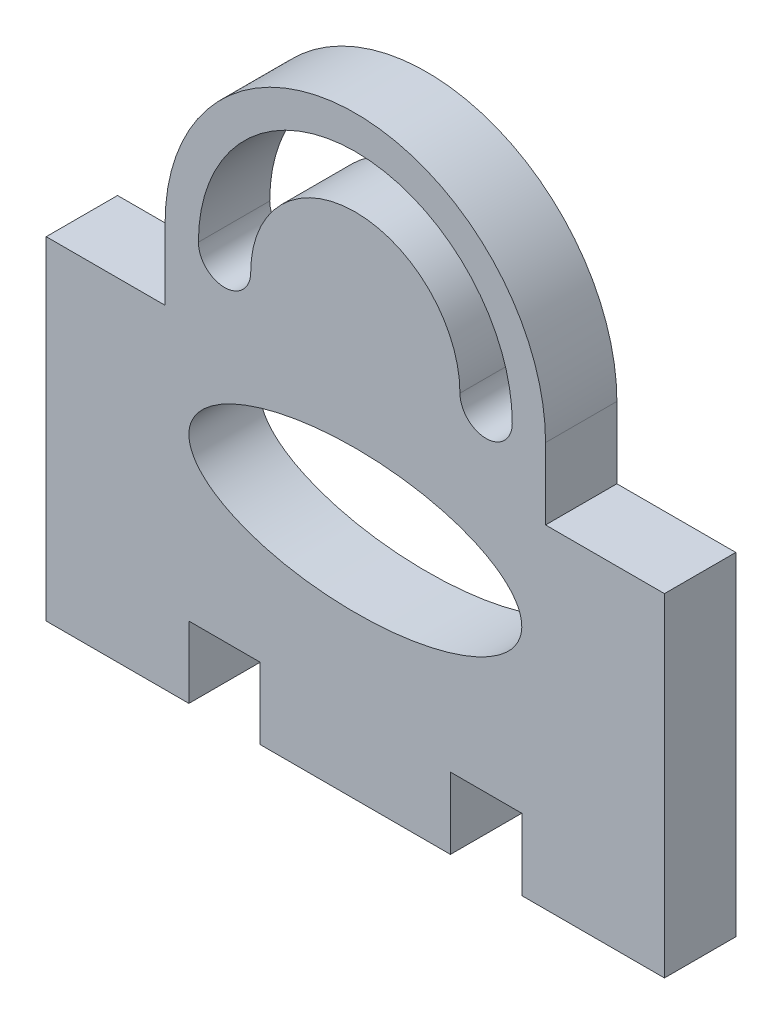
SolidWorks part; units mm, degrees
ref_plane "Front Plane" through (0, 0, 0) normal (0, 0, 1) x (1, 0, 0)
ref_plane "Top Plane" through (0, 0, 0) normal (0, 1, 0) x (1, 0, 0)
ref_plane "Right Plane" through (0, 0, 0) normal (1, 0, 0) x (0, 0, -1)
sketch "Sketch1" plane through (0, 0, 0) normal (0, 0, 1) x (1, 0, 0)
  line L0 (130, -70) -> (70, -70)
  line L2 (130, -70) -> (130, 70)
  line L3 (130, 70) -> (80, 70)
  line L4 (-130, -70) -> (-130, 70)
  line L5 (40, -40) -> (40, -70)
  line L6 (70, -40) -> (70, -70)
  line L8 (-130, -70) -> (-70, -70)
  line L9 (70, -40) -> (40, -40)
  line L10 (40, -70) -> (-40, -70)
  line L11 (-70, -70) -> (-70, -40)
  line L13 (-40, -70) -> (-40, -40)
  line L14 (-40, -40) -> (-70, -40)
  line L16 (0, 0) -> (0, 232.6311) construction
  line L17 (-80, 70) -> (-130, 70)
  line L18 (-80, 100) -> (-80, 70)
  line L19 (80, 100) -> (80, 70)
  line L20 (-149.4428, 28.0053) -> (199.022, 28.0053) construction
  arc A1 (80, 100) -> (-80, 100) centre (0, 100) ccw
  arc A2 (-55, 100) -> (55, 100) centre (0, 100) cw construction
  arc A3 (66, 100) -> (-66, 100) centre (0, 100) ccw
  arc A4 (44, 100) -> (-44, 100) centre (0, 100) ccw
  arc A5 (44, 100) -> (66, 100) centre (55, 100) ccw
  arc A6 (-66, 100) -> (-44, 100) centre (-55, 100) ccw
  ellipse E0 centre (0, 28.0053) end of major axis (-70, 28.0053) minor radius 30
  point P0 (0, 0)
  point P26 (0, 164.5804)
  point P32 (0, 0)
  dimension "D10" = 160
  dimension "D12" = 22
  dimension "D11" = 55
  dimension "D1" = 140
  dimension "D2" = 260
  dimension "D3" = 60
  dimension "D5" = 260
  dimension "D6" = 260
  dimension "D7" = 30
  dimension "D8" = 60
  dimension "D9" = 30
extrude "Boss-Extrude1" add sketch "Sketch1" along normal blind 30
